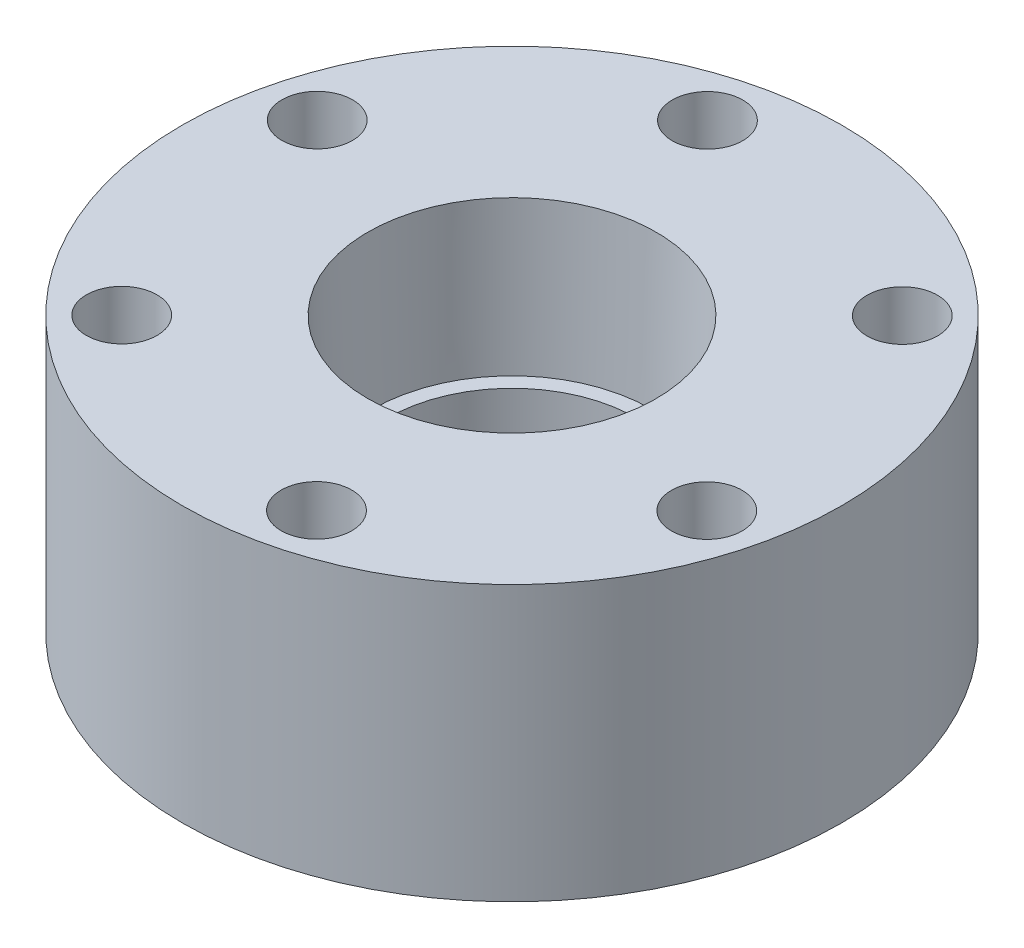
SolidWorks part; units mm, degrees
material "AISI 316 Stainless Steel Sheet (SS)"
ref_plane "Front Plane" through (0, 0, 0) normal (0, 0, 1) x (1, 0, 0)
ref_plane "Top Plane" through (0, 0, 0) normal (0, 1, 0) x (1, 0, 0)
ref_plane "Right Plane" through (0, 0, 0) normal (1, 0, 0) x (0, 0, -1)
sketch "Sketch1" plane through (0, 0, 0) normal (0, 1, 0) x (1, 0, 0)
  circle A0 centre (0, 0) radius 30.48
  dimension "D1" = 60.96
extrude "Boss-Extrude1" add sketch "Sketch1" along normal blind 25.4
sketch "Sketch2" plane through (0, 0, 0) normal (0, -1, 0) x (1, 0, 0)
  circle A0 centre (0, 0) radius 20.6502
  dimension "D1" = 41.3004
extrude "Cut-Extrude1" cut sketch "Sketch2" against normal blind 6.35
hole_wizard "3/4 NPT Tapped Hole1" positions "Sketch3" profile "Sketch4" size "3/4" standard "ANSI Inch" end condition through all
sketch "Sketch3" plane through (0, 25.4, 0) normal (0, 1, 0) x (1, 0, 0)
  point P0 (0, 0)
sketch "Sketch4" plane through (0, 25.4, 0) normal (1, 0, 0) x (0, 0, 1)
  line L0 (0, 0) -> (0, 25.4)
  line L1 (0, 25.4) -> (11.5062, 25.4)
  line L2 (-12.9142, 13.97) -> (-13.3325, 0) construction
  line L3 (11.5062, 25.4) -> (11.5062, 13.97)
  line L4 (11.5062, 13.97) -> (12.9142, 13.97)
  line L5 (12.9142, 13.97) -> (13.3325, 0)
  line L7 (13.3325, 0) -> (0, 0)
  line L8 (0, -6.35) -> (0, 107.95) construction
  line L11 (-11.5062, 13.97) -> (-12.9142, 13.97) construction
  dimension "Thru Tap Drill Dia." = 23.0124
  dimension "Thru Tap Drill Depth" = 25.4
  dimension "Thread Dia." = 26.665
  dimension "Thread Angle" = 3.43
  dimension "Thread Depth" = 13.97
hole_wizard "1/4 Clearance Hole1" positions "Sketch5" profile "Sketch6" hole size "1/4" standard "ANSI Inch" end condition through all
sketch "Sketch5" plane through (0, 25.4, 0) normal (0, 1, 0) x (1, 0, 0)
  point P0 (-24.6365, 6.6279)
  point P3 (-18.0582, -18.0219)
  point P6 (6.5783, -24.6498)
  point P12 (24.6365, -6.6279)
  point P15 (18.0582, 18.0219)
  point P18 (-6.5783, 24.6498)
  point P22 (0, 0)
sketch "Sketch6" plane through (-24.6365, 25.4, -6.6279) normal (1, 0, 0) x (0, 0, 1)
  line L0 (0, 0) -> (0, 25.4)
  line L1 (0, 25.4) -> (3.2639, 25.4)
  line L2 (3.2639, 25.4) -> (3.2639, 0)
  line L5 (3.2639, 0) -> (0, 0)
  line L11 (0, -6.35) -> (0, 107.95) construction
  dimension "Thru Hole Dia." = 6.5278
  dimension "Thru Hole Depth" = 25.4
